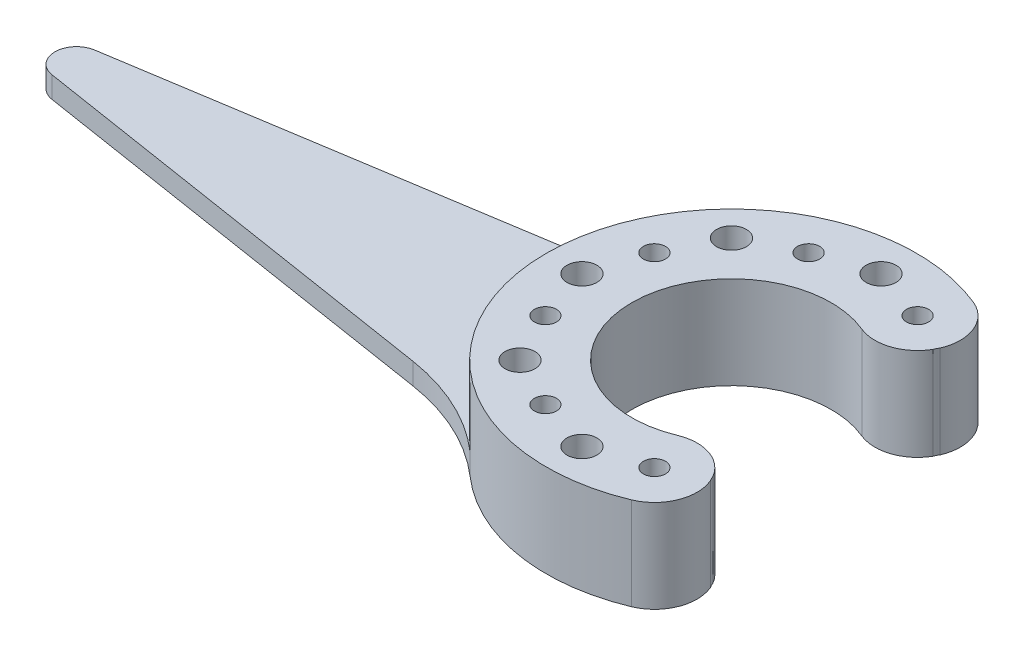
SolidWorks part; units mm, degrees
ref_plane "Front Plane" through (0, 0, 0) normal (0, 0, 1) x (1, 0, 0)
ref_plane "Top Plane" through (0, 0, 0) normal (0, 1, 0) x (1, 0, 0)
ref_plane "Right Plane" through (0, 0, 0) normal (1, 0, 0) x (0, 0, -1)
sketch "Sketch4" plane through (0, 0, 3) normal (0, -1, 0) x (1, 0, 0)
  line L0 (0, 18) -> (0, -3) construction
  line L1 (0, -3) -> (7.6537, 15.4776) construction
  circle A0 centre (0, 18) radius 2.1
  circle A1 centre (7.6537, 15.4776) radius 1.55
  circle A2 centre (14.8492, 11.8492) radius 2.1
  circle A3 centre (18.4776, 4.6537) radius 1.55
  circle A4 centre (21, -3) radius 2.1
  circle A5 centre (18.4776, -10.6537) radius 1.55
  circle A6 centre (14.8492, -17.8492) radius 2.1
  circle A7 centre (7.6537, -21.4776) radius 1.55
  circle A8 centre (0, -24) radius 2.1
  circle A9 centre (-7.6537, -21.4776) radius 1.55
  circle A10 centre (-14.8492, -17.8492) radius 2.1
  circle A11 centre (-18.4776, -10.6537) radius 1.55
  circle A12 centre (-21, -3) radius 2.1
  circle A13 centre (-18.4776, 4.6537) radius 1.55
  circle A14 centre (-14.8492, 11.8492) radius 2.1
  circle A15 centre (-7.6537, 15.4776) radius 1.55
  circle A16 centre (0, -3) radius 26
  point P37 (0, -3)
  dimension "D2" = 4.2
  dimension "D3" = 3.1
  dimension "D7" = 52
  dimension "D1" = 22.5
  dimension "D4" = 21
  dimension "D5" = 20
  dimension "D6" = 8
extrude "Boss-Extrude1" add sketch "Sketch4" along normal blind 13
sketch "Sketch5" plane through (0, -13, 0) normal (0, -1, 0) x (1, 0, 0)
  arc A0 (5.3576, 12.9343) -> (5.3576, -12.9343) centre (0, 0) ccw
  circle A1 centre (0, 0) radius 26 construction
  arc A2 (9.9498, 24.0209) -> (9.9498, -24.0209) centre (0, 0) ccw
  arc A3 (5.3576, 12.9343) -> (9.9498, 24.0209) centre (7.6537, 18.4776) ccw
  arc A4 (9.9498, -24.0209) -> (5.3576, -12.9343) centre (7.6537, -18.4776) ccw
extrude "Cut-Extrude1" cut sketch "Sketch5" against normal through all flip side to cut
sketch "Sketch6" plane through (0, -13, 0) normal (0, -1, 0) x (1, 0, 0)
  line L0 (-26, 0) -> (-95, 0) construction
  line L1 (-92.4361, 3) -> (-32.2139, 12.5)
  line L2 (-92.4361, -3) -> (-32.2139, -12.5)
  arc A0 (9.9498, 24.0209) -> (9.9498, -24.0209) centre (0, 0) ccw construction
  arc A1 (-92.4361, -3) -> (-92.4361, 3) centre (-91.9629, 0) cw
  arc A2 (-32.2139, 12.5) -> (-17.1268, 19.562) centre (-36.8885, 42.1336) ccw
  arc A3 (-17.1268, 19.562) -> (-17.1268, -19.562) centre (0, 0) ccw
  arc A4 (-32.2139, -12.5) -> (-17.1268, -19.562) centre (-36.8885, -42.1336) cw
  point P12 (-36.5, 12.5)
  point P13 (-42.3262, 12.5)
  point P14 (-30.0794, 12.5)
  dimension "D3" = 30
  dimension "D1" = 6
  dimension "D2" = 95
  dimension "D4" = 25
extrude "Boss-Extrude2" add sketch "Sketch6" against normal blind 3
